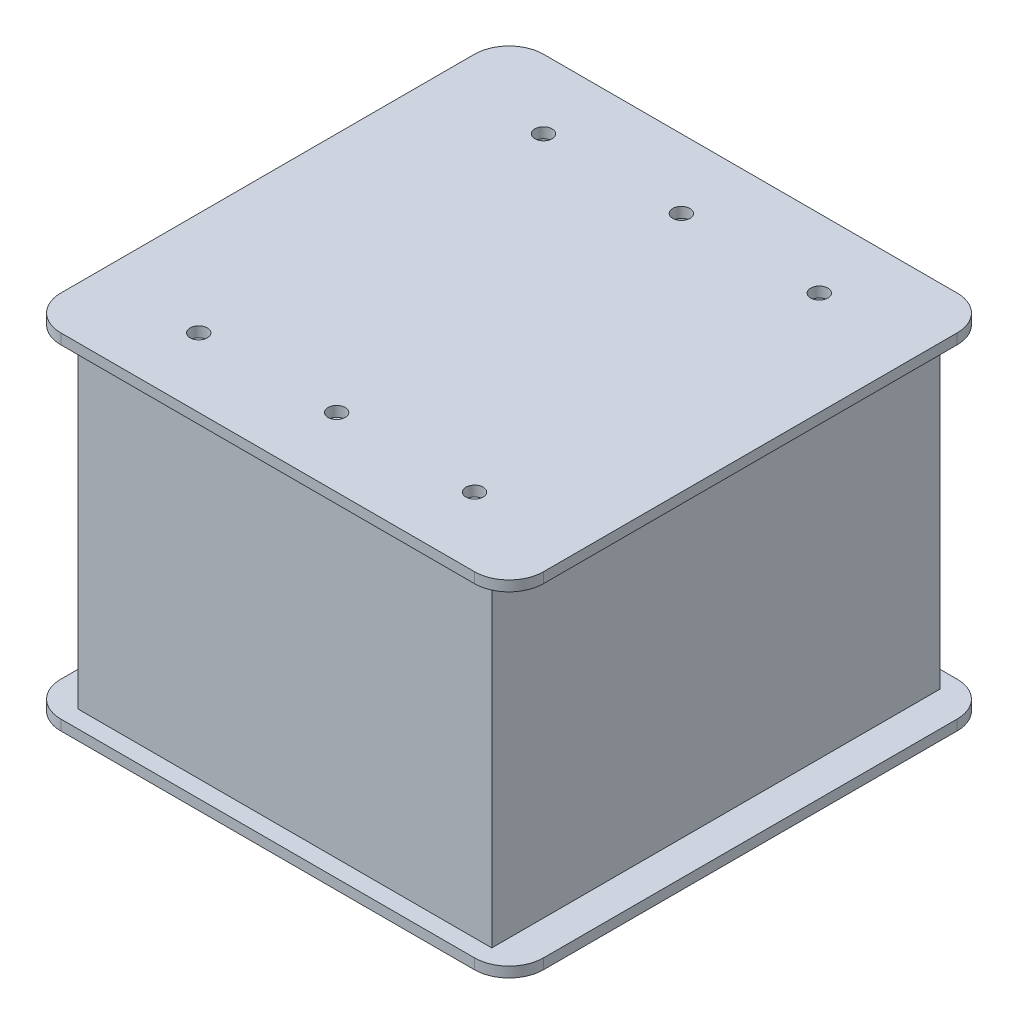
SolidWorks part; units mm, degrees
ref_plane "Front Plane" through (0, 0, 0) normal (0, 0, 1) x (1, 0, 0)
ref_plane "Top Plane" through (0, 0, 0) normal (0, 1, 0) x (1, 0, 0)
ref_plane "Right Plane" through (0, 0, 0) normal (1, 0, 0) x (0, 0, -1)
sketch "Sketch1" plane through (0, 0, 0) normal (0, 1, 0) x (1, 0, 0)
  line L1 (60, 70) -> (-60, 70)
  line L2 (70, 60) -> (70, -60)
  line L3 (60, -70) -> (-60, -70)
  line L4 (-70, 60) -> (-70, -60)
  line L5 (0, -70) -> (0, 70) construction
  line L6 (70, 0) -> (-70, 0) construction
  circle A0 centre (-40, 50) radius 2.5
  circle A1 centre (0, 50) radius 2.5
  circle A2 centre (40, 50) radius 2.5
  circle A3 centre (-40, -50) radius 2.5
  circle A4 centre (0, -50) radius 2.5
  circle A5 centre (40, -50) radius 2.5
  arc A6 (-60, -70) -> (-70, -60) centre (-60, -60) cw
  arc A7 (70, -60) -> (60, -70) centre (60, -60) cw
  arc A8 (60, 70) -> (70, 60) centre (60, 60) cw
  arc A9 (-60, 70) -> (-70, 60) centre (-60, 60) ccw
  point P0 (0, 0)
  point P10 (46.9697, 78.3346)
  point P11 (0, 0)
  point P12 (0, 50)
  point P13 (80.7197, 63.125)
  point P24 (70, -70)
  point P27 (70, 70)
  point P30 (-70, 70)
  dimension "D1" = 5
  dimension "D2" = 40
  dimension "D3" = 40
  dimension "D4" = 50
  dimension "D7" = 10
  dimension "D5" = 140
  dimension "D6" = 140
extrude "Boss-Extrude1" add sketch "Sketch1" along normal blind 3
sketch "Sketch2" plane through (0, 3, 0) normal (0, 1, 0) x (1, 0, 0)
  line L0 (60, 70) -> (-60, 70) construction
  line L1 (-60, 65) -> (60, 65)
  line L3 (-57, 62) -> (57, 62)
  line L5 (0, 0) -> (95.2694, 0) construction
  line L7 (-57, -62) -> (57, -62)
  line L9 (-60, -65) -> (60, -65)
  line L10 (-60, -70) -> (60, -70) construction
  line L12 (-60, 65) -> (-60, -65)
  line L14 (-57, 62) -> (-57, -62)
  line L16 (60, -65) -> (60, 65)
  line L18 (57, -62) -> (57, 62)
  point P1 (62.3491, 65)
  point P2 (-64.0896, 65)
  point P6 (0, 62)
  point P11 (63.8994, -65)
  point P12 (-66.8943, -65)
  point P14 (0, 0)
  point P16 (-60, 72.0774)
  point P17 (60, 62)
  dimension "D1" = 3
  dimension "D2" = 5
  dimension "D3" = 120
  dimension "D4" = 3
  dimension "D5" = 3
  dimension "D6" = 5
  dimension "D7" = 3
extrude "Boss-Extrude2" add sketch "Sketch2" along normal blind 94
sketch "Sketch3" plane through (0, 97, 0) normal (0, 1, 0) x (1, 0, 0)
  line L4 (60, 70) -> (-60, 70)
  line L5 (-70, 60) -> (-70, -60)
  line L6 (-60, -70) -> (60, -70)
  line L7 (70, -60) -> (70, 60)
  line L8 (60, 70) -> (-60, 70)
  line L9 (-70, 60) -> (-70, -60)
  line L10 (-60, -70) -> (60, -70)
  line L11 (70, -60) -> (70, 60)
  circle A1 centre (-40, -50) radius 2.5
  circle A2 centre (-40, -50) radius 2.5
  circle A3 centre (40, 50) radius 2.5
  circle A4 centre (40, 50) radius 2.5
  circle A5 centre (0, 50) radius 2.5
  circle A6 centre (0, 50) radius 2.5
  circle A7 centre (-40, 50) radius 2.5
  circle A8 centre (-40, 50) radius 2.5
  circle A9 centre (40, -50) radius 2.5
  circle A10 centre (40, -50) radius 2.5
  circle A11 centre (0, -50) radius 2.5
  circle A12 centre (0, -50) radius 2.5
  arc A16 (-60, 70) -> (-70, 60) centre (-60, 60) ccw
  arc A17 (-70, -60) -> (-60, -70) centre (-60, -60) ccw
  arc A18 (60, -70) -> (70, -60) centre (60, -60) ccw
  arc A19 (70, 60) -> (60, 70) centre (60, 60) ccw
  arc A20 (-60, 70) -> (-70, 60) centre (-60, 60) ccw
  arc A21 (-70, -60) -> (-60, -70) centre (-60, -60) ccw
  arc A22 (60, -70) -> (70, -60) centre (60, -60) ccw
  arc A23 (70, 60) -> (60, 70) centre (60, 60) ccw
  dimension "D1" = 0
  dimension "D2" = 0
  dimension "D3" = 0
  dimension "D4" = 0
  dimension "D5" = 0
  dimension "D6" = 0
  dimension "D7" = 0
extrude "Boss-Extrude3" add sketch "Sketch3" along normal blind 3
sketch "Sketch5" plane through (60, 0, 0) normal (1, 0, 0) x (0, 0, -1)
  line L0 (-65, 3) -> (65, 3) construction
  line L1 (-65, 97) -> (-65, 3) construction
  circle A0 centre (-45, 13) radius 10
  point P2 (-46.4645, 10.6981)
  dimension "D1" = 20
  dimension "D2" = 20
extrude "Boss-Extrude6" add sketch "Sketch5" against normal blind 114 from surface at -3 separate body starting at face at (57, 50, 0)
pattern_linear "LPattern1" count 5 spacing 22 along (0, 0, -1) count 4 spacing 24 along (0, 1, 0) of "Boss-Extrude6"
